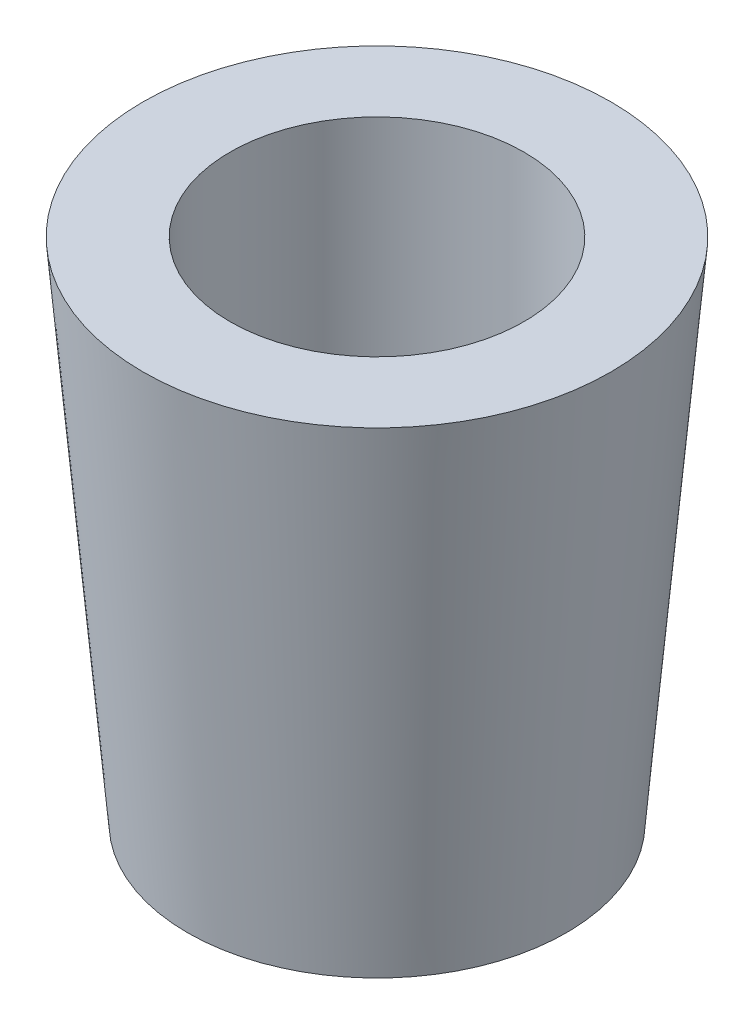
SolidWorks part; units mm, degrees
material "Brass"
ref_plane "Front Plane" through (0, 0, 0) normal (0, 0, 1) x (1, 0, 0)
ref_plane "Top Plane" through (0, 0, 0) normal (0, 1, 0) x (1, 0, 0)
ref_plane "Right Plane" through (0, 0, 0) normal (1, 0, 0) x (0, 0, -1)
sketch "Sketch1" plane through (0, 0, 0) normal (0, 1, 0) x (1, 0, 0)
  circle A0 centre (0, 0) radius 11.7
  dimension "D1" = 23.4
extrude "Boss-Extrude1" add sketch "Sketch1" against normal blind 25.4 draft 5
sketch "Sketch2" plane through (0, 0, 0) normal (0, 1, 0) x (1, 0, 0)
  circle A0 centre (0, 0) radius 3.175
  dimension "D1" = 6.35
extrude "Cut-Extrude1" cut sketch "Sketch2" against normal through all
sketch "Sketch3" plane through (0, 0, 0) normal (0, 0, 1) x (1, 0, 0)
  line L0 (0, -28.4383) -> (0, 0) construction
sketch "Sketch8" plane through (0, 0, 0) normal (0, 1, 0) x (1, 0, 0)
sketch "Sketch9" plane through (0, 0, 0) normal (0, 1, 0) x (1, 0, 0)
  circle A0 centre (0, 0) radius 7.35
  dimension "D1" = 14.7
extrude "Cut-Extrude3" cut sketch "Sketch9" against normal blind 12.7
sketch "Sketch14" plane through (0, -25.4, 0) normal (0, -1, 0) x (1, 0, 0)
  line L0 (-8.4778, -13.7119) -> (-8.4778, 12.3381) construction
  line L1 (-3.175, -14.7917) -> (-3.175, 13.2154) construction
  circle A0 centre (-5.8264, 0) radius 1.75
  circle A1 centre (0, 0) radius 3.175 construction
  circle A2 centre (0, 5.8264) radius 1.75
  circle A3 centre (5.8264, 0) radius 1.75
  circle A4 centre (0, -5.8264) radius 1.75
  circle A5 centre (0, 0) radius 8.4778
  circle A6 centre (0, 0) radius 8.4778
  point P20 (0, 0)
  dimension "D1" = 3.5
  dimension "D2" = 2.6514
  dimension "D3" = 5.3028
  dimension "D4" = 1
  dimension "D5" = 4
extrude "Cut-Extrude5" cut sketch "Sketch14" against normal blind 7.62 contours A2 | A0 | A4 | A3
sketch "Sketch13" plane through (0, -25.4, 0) normal (0, -1, 0) x (1, 0, 0)
  line L0 (-3.175, 0) -> (-3.175, 6.015) construction
  line L1 (-9.4778, 0) -> (-9.4778, 6.015) construction
  line L2 (0, 0) -> (-6.3264, 0) construction
  line L3 (0, 0) -> (3.1632, 5.4788) construction
  circle A0 centre (-6.3264, 0) radius 2
  circle A1 centre (0, 0) radius 3.175 construction
  circle A2 centre (0, 0) radius 9.4778 construction
  circle A3 centre (-5.4788, 3.1632) radius 2
  circle A4 centre (3.1632, 5.4788) radius 2
  circle A5 centre (3.1632, -5.4788) radius 2
  circle A6 centre (-5.4788, -3.1632) radius 2
  point P14 (0, 0)
  dimension "D1" = 3.1514
  dimension "D3" = 4
  dimension "D4" = 2
  dimension "D2" = 6.3028
  dimension "D6" = 120
  dimension "D5" = 2
extrude "Cut-Extrude4" [suppressed] cut sketch "Sketch13" against normal blind 7.62 contours A5 | A3 | A6 | A4
equation "\"D1@Sketch7\" = \"D1@Sketch1\" / 10"
equation "\"D2@Sketch7\" = ( \"D1@Sketch1\" / 2 )"
equation "\"D1@Sketch13\" = \"D2@Sketch13\" / 2"
equation "\"D2@Sketch14\" = \"D3@Sketch14\" / 2"
